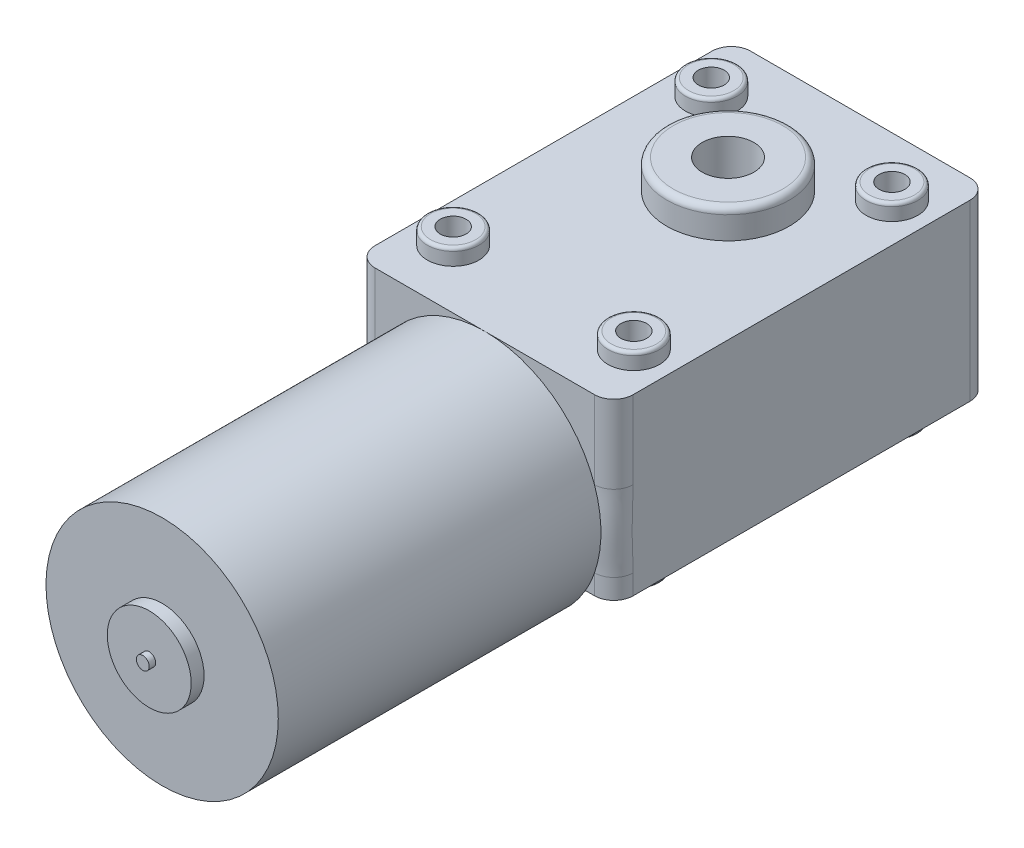
SolidWorks part; units mm, degrees
ref_plane "Front Plane" through (0, 0, 0) normal (0, 0, 1) x (1, 0, 0)
ref_plane "Top Plane" through (0, 0, 0) normal (0, 1, 0) x (1, 0, 0)
ref_plane "Right Plane" through (0, 0, 0) normal (1, 0, 0) x (0, 0, -1)
sketch "Sketch1" plane through (0, 0, 0) normal (0, 1, 0) x (1, 0, 0)
  line L0 (0, 29.1) -> (0, -29.1) construction
  line L1 (-20, 29.1) -> (20, 29.1)
  line L2 (-20, 29.1) -> (-20, -29.1)
  line L3 (-20, -29.1) -> (20, -29.1)
  line L4 (20, 29.1) -> (20, -29.1)
  line L5 (-20, 29.1) -> (20, -29.1) construction
  line L6 (-20, -29.1) -> (20, 29.1) construction
  line L7 (-14, 20) -> (14, 20) construction
  line L8 (-14, 20) -> (-14, -20) construction
  line L9 (-14, -20) -> (14, -20) construction
  line L10 (14, 20) -> (14, -20) construction
  line L11 (-14, 20) -> (14, -20) construction
  line L12 (-14, -20) -> (14, 20) construction
  circle A0 centre (-14, 20) radius 2
  circle A1 centre (14, 20) radius 2
  circle A2 centre (14, -20) radius 2
  circle A3 centre (-14, -20) radius 2
  circle A4 centre (0, 8.6) radius 4
  point P0 (0, 0)
  point P6 (0, 0)
  dimension "D5" = 4
  dimension "D6" = 4
  dimension "D7" = 4
  dimension "D8" = 4
  dimension "D9" = 8
  dimension "D10" = 20.5
  dimension "D1" = 58.2
  dimension "D2" = 40
  dimension "D3" = 28
  dimension "D4" = 40
extrude "Boss-Extrude1" add sketch "Sketch1" along normal blind 27
sketch "Sketch2" plane through (0, 27, 0) normal (0, 1, 0) x (1, 0, 0)
  circle A0 centre (0, 8.6) radius 4
  circle A1 centre (0, 8.6) radius 9.5
  dimension "D1" = 8
  dimension "D2" = 19
extrude "Boss-Extrude2" add sketch "Sketch2" along normal blind 4.5
sketch "Sketch3" plane through (0, 0, 0) normal (0, -1, 0) x (1, 0, 0)
  circle A0 centre (0, -8.6) radius 4
  circle A1 centre (0, -8.6) radius 9.5
  dimension "D1" = 8
  dimension "D2" = 19
extrude "Boss-Extrude3" add sketch "Sketch3" along normal blind 4.5
sketch "Sketch4" plane through (0, 27, 0) normal (0, 1, 0) x (1, 0, 0)
  line L0 (0, 29.1) -> (0, -29.1) construction
  line L1 (20, 29.1) -> (-20, 29.1) construction
  line L2 (-20, -29.1) -> (20, -29.1) construction
  line L3 (-20, 0) -> (20, 0) construction
  line L4 (-20, 29.1) -> (-20, -29.1) construction
  line L5 (20, -29.1) -> (20, 29.1) construction
  circle A0 centre (-14, 20) radius 2
  circle A1 centre (-14, 20) radius 4
  circle A2 centre (-14, -20) radius 2
  circle A3 centre (-14, -20) radius 4
  circle A4 centre (14, -20) radius 4
  circle A5 centre (14, -20) radius 2
  circle A6 centre (14, 20) radius 2
  circle A7 centre (14, 20) radius 4
  dimension "D1" = 4
  dimension "D2" = 8
extrude "Boss-Extrude4" add sketch "Sketch4" along normal blind 2.5
sketch "Sketch5" plane through (0, 0, 0) normal (0, -1, 0) x (1, 0, 0)
  line L0 (0, 29.1) -> (0, -29.1) construction
  line L1 (-20, 29.1) -> (20, 29.1) construction
  line L2 (20, -29.1) -> (-20, -29.1) construction
  line L3 (-20, 0) -> (20, 0) construction
  line L4 (-20, -29.1) -> (-20, 29.1) construction
  line L5 (20, 29.1) -> (20, -29.1) construction
  circle A0 centre (-14, 20) radius 2
  circle A1 centre (-14, 20) radius 4
  circle A2 centre (14, 20) radius 4
  circle A3 centre (14, 20) radius 2
  circle A4 centre (14, -20) radius 2
  circle A5 centre (14, -20) radius 4
  circle A6 centre (-14, -20) radius 4
  circle A7 centre (-14, -20) radius 2
  dimension "D1" = 4
  dimension "D2" = 8
extrude "Boss-Extrude5" add sketch "Sketch5" along normal blind 2.5
sketch "Sketch6" plane through (0, 0, 29.1) normal (0, 0, 1) x (1, 0, 0)
  line L0 (0, 27) -> (0, 0) construction
  line L1 (-20, 27) -> (20, 27) construction
  circle A0 centre (0, 9) radius 18
  dimension "D1" = 36
extrude "Boss-Extrude6" add sketch "Sketch6" along normal blind 50
sketch "Sketch7" plane through (0, 0, 79.1) normal (0, 0, 1) x (1, 0, 0)
  circle A0 centre (0, 9) radius 6.5
  dimension "D1" = 13
extrude "Boss-Extrude7" add sketch "Sketch7" along normal blind 2
sketch "Sketch8" plane through (0, 0, 81.1) normal (0, 0, 1) x (1, 0, 0)
  circle A0 centre (0, 9) radius 1
  dimension "D1" = 2
extrude "Boss-Extrude8" add sketch "Sketch8" along normal blind 1
fillet "Fillet1" radius 3 4 edges at (-20, 13.5, -29.1) (-20, 13.5, 29.1) (20, 13.5, 29.1) (20, 13.5, -29.1)
fillet "Fillet2" radius 1 2 edges at (0, -4.5, -18.1) (0, 31.5, 0.9)
fillet "Fillet3" radius 0.5 8 edges at (-14, -2.5, 16) (-14, -2.5, -16) (14, -2.5, -24) (14, -2.5, 24) (14, 29.5, -24) (-14, 29.5, -16) (14, 29.5, 24) (-14, 29.5, 16)
